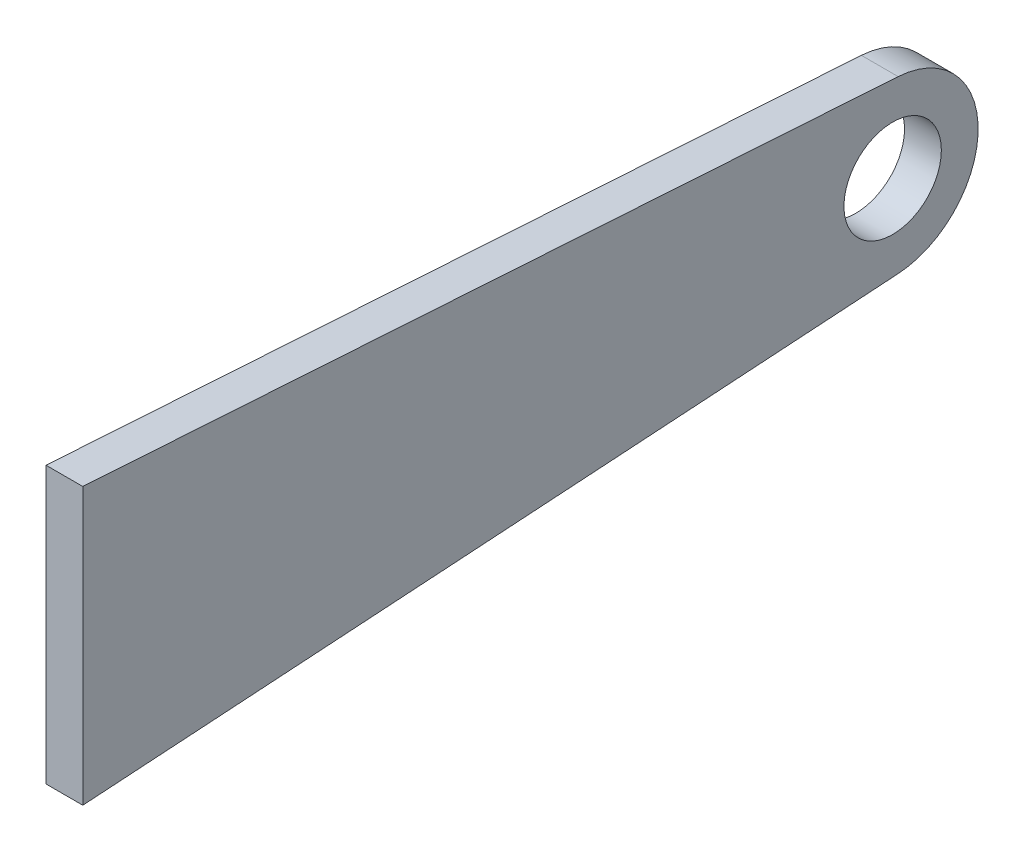
SolidWorks part; units mm, degrees
material "AISI 4130 Steel, annealed at 865C"
ref_plane "X-Y Datum" through (0, 0, 0) normal (0, 0, 1) x (1, 0, 0)
ref_plane "X-Z Datum" through (0, 0, 0) normal (0, 1, 0) x (1, 0, 0)
ref_plane "Y-Z Datum" through (0, 0, 0) normal (1, 0, 0) x (0, 0, -1)
sketch "Sketch1" plane through (0, 0, 0) normal (1, 0, 0) x (0, 0, -1)
  line L0 (0, 0) -> (-69.85, 0) construction
  line L1 (-69.85, 11.9062) -> (-69.85, -11.9063)
  line L2 (0.4758, -7.3596) -> (-69.85, -11.9063)
  line L3 (0.4758, 7.3596) -> (-69.85, 11.9062)
  circle A0 centre (0, 0) radius 4.2
  arc A1 (0.4758, -7.3596) -> (0.4758, 7.3596) centre (0, 0) ccw
  point P7 (-69.85, 0)
  dimension "D1" = 8.4
  dimension "D2" = 3.175
  dimension "D3" = 69.85
  dimension "D4" = 23.8125
extrude "Boss-Extrude1" add sketch "Sketch1" along normal mid plane 3.175 contours L2 L1 L3 A1
